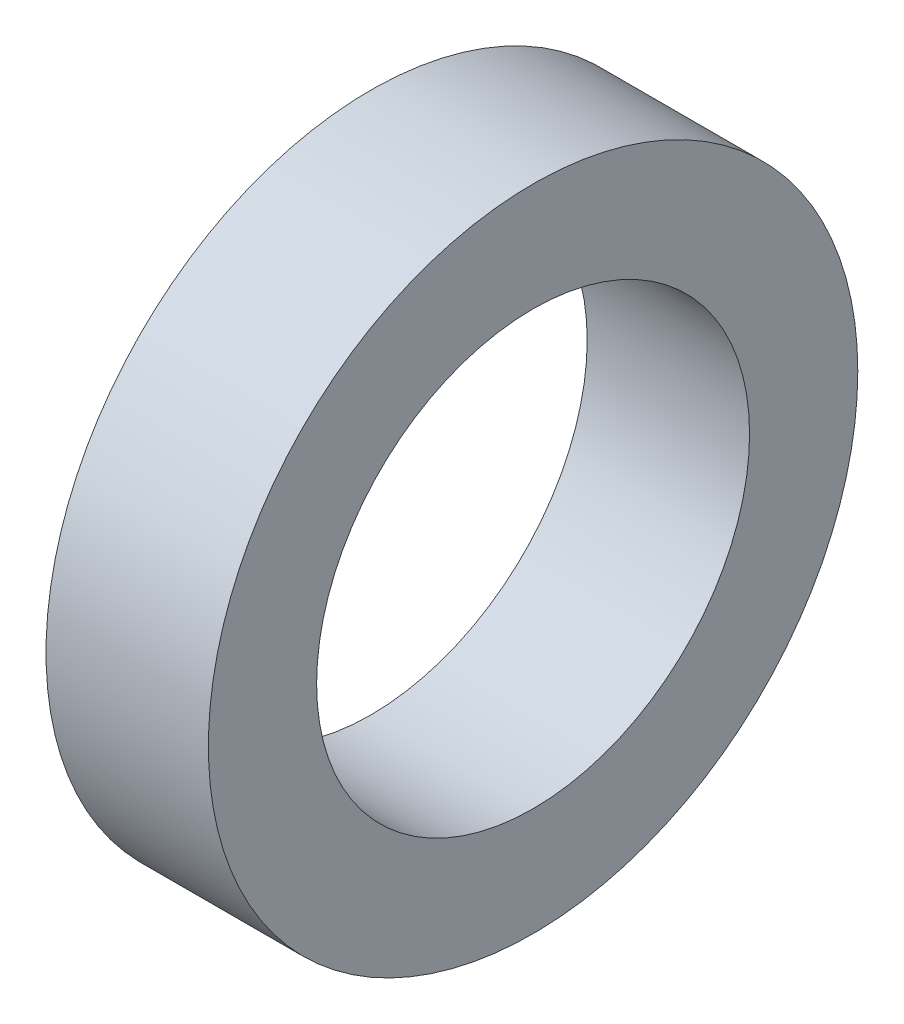
SolidWorks part; units mm, degrees
material "AISI 304"
ref_plane "Front Plane" through (0, 0, 0) normal (0, 0, 1) x (1, 0, 0)
ref_plane "Top Plane" through (0, 0, 0) normal (0, 1, 0) x (1, 0, 0)
ref_plane "Right Plane" through (0, 0, 0) normal (1, 0, 0) x (0, 0, -1)
sketch "Sketch1" plane through (0, 0, 0) normal (1, 0, 0) x (0, 0, -1)
  circle A0 centre (0, 0) radius 4
  circle A1 centre (0, 0) radius 6
  dimension "D1" = 8
  dimension "D2" = 12
extrude "Boss-Extrude1" add sketch "Sketch1" along normal blind 3
